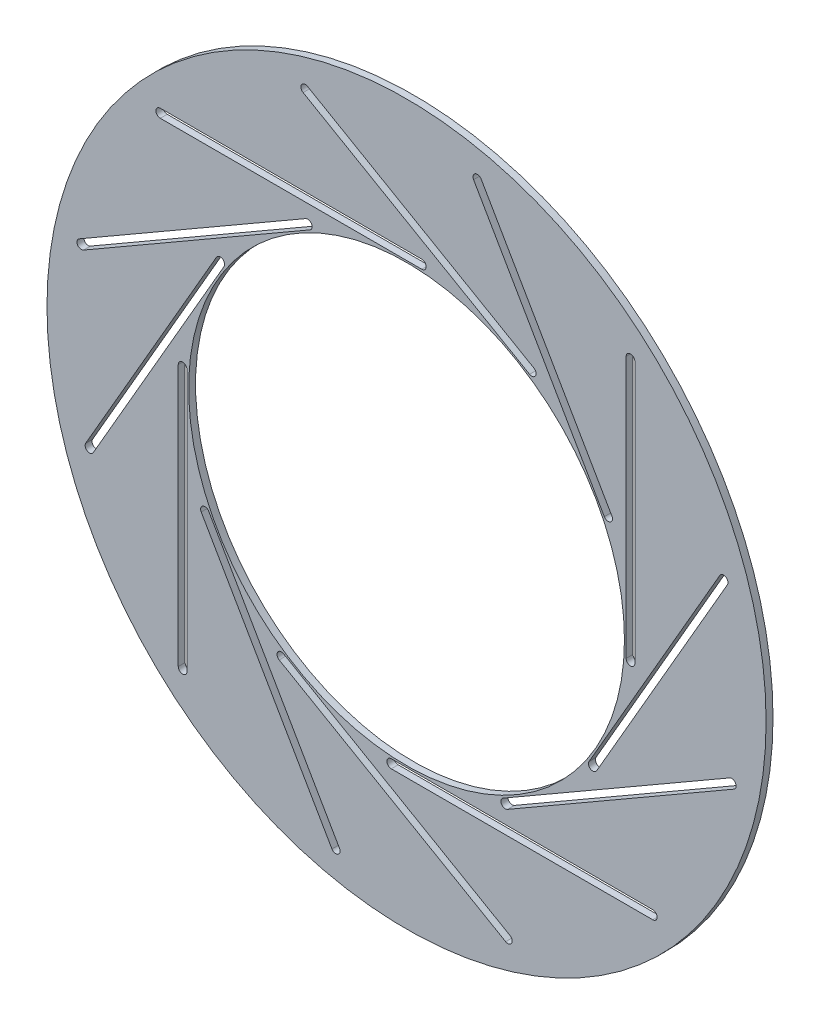
SolidWorks part; units mm, degrees
ref_plane "Front Plane" through (0, 0, 0) normal (0, 0, 1) x (1, 0, 0)
ref_plane "Top Plane" through (0, 0, 0) normal (0, 1, 0) x (1, 0, 0)
ref_plane "Right Plane" through (0, 0, 0) normal (1, 0, 0) x (0, 0, -1)
sketch "Sketch1" plane through (0, 0, 0) normal (0, 0, 1) x (1, 0, 0)
  circle A0 centre (0, 0) radius 100
  circle A1 centre (0, 0) radius 165
  dimension "D1" = 330
  dimension "D2" = 200
extrude "Boss-Extrude1" add sketch "Sketch1" along normal blind 3.175
sketch "Sketch2" plane through (0, 0, 3.175) normal (0, 0, 1) x (1, 0, 0)
  line L0 (0, 0) -> (0, 103) construction
  line L1 (-113, 102.7619) -> (7, 102.7619) construction
  line L2 (-113, 104.7619) -> (7, 104.7619)
  line L3 (-113, 100.7619) -> (7, 100.7619)
  circle A0 centre (0, 0) radius 103 construction
  arc A1 (-113, 104.7619) -> (-113, 100.7619) centre (-113, 102.7619) ccw
  arc A2 (7, 100.7619) -> (7, 104.7619) centre (7, 102.7619) ccw
  point P6 (-53, 102.7619)
  dimension "D1" = 2
  dimension "D4" = 206
  dimension "D2" = 7
  dimension "D5" = 120
extrude "Cut-Extrude1" cut sketch "Sketch2" against normal blind 3.175
pattern_circular "CirPattern1" count 12 over 360 about axis through (0, 0, 0) along (0, 0, 1) of "Cut-Extrude1"
